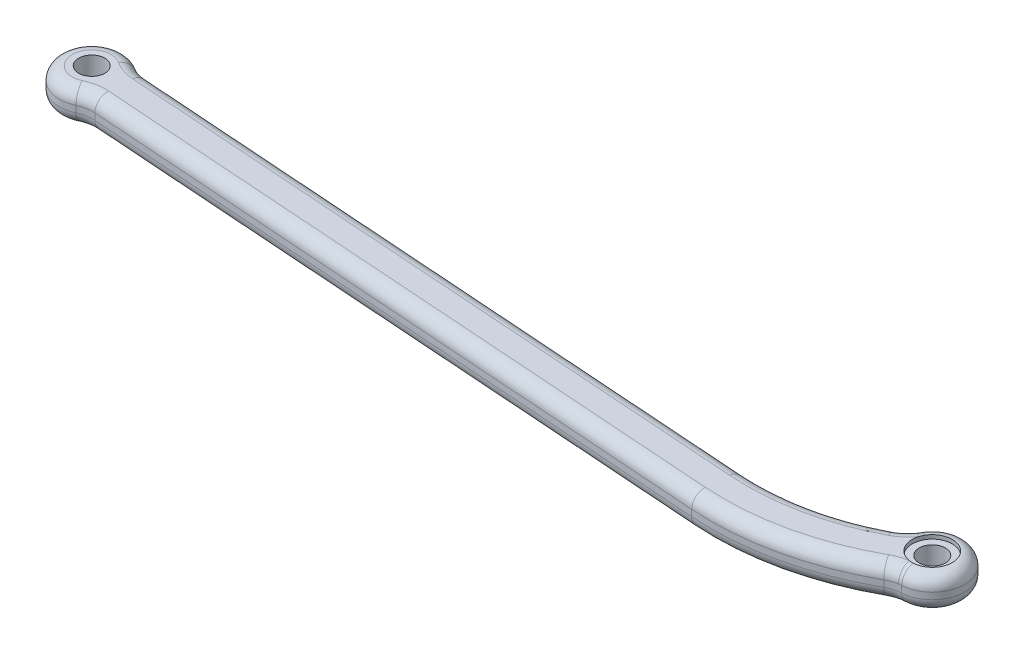
SolidWorks part; units mm, degrees
material "ABS PC"
ref_plane "Alzado" through (0, 0, 0) normal (1, 0, 0) x (0, 1, 0)
ref_plane "Planta" through (0, 0, 0) normal (0, 0, 1) x (0, 1, 0)
ref_plane "Vista lateral" through (0, 0, 0) normal (0, 1, 0) x (-1, 0, 0)
sketch "Croquis1" plane through (0, 0, 0) normal (0, 1, 0) x (-1, 0, 0)
  line L0 (0, 0) -> (260, 0) construction
  line L1 (51.8656, 14.5542) -> (260, 0) construction
  line L2 (52.3888, 22.0359) -> (260.5232, 7.4817)
  line L3 (51.3425, 7.0724) -> (259.4768, -7.4817)
  line L4 (260, 0) -> (51.8656, 14.5542) construction
  line L9 (130, -7.5) -> (130, 0) construction
  line L10 (0, 0) -> (46.2851, -65.251) construction
  line L11 (46.2851, -65.251) -> (51.8656, 14.5542) construction
  circle A0 centre (0, 0) radius 4.05
  circle A1 centre (260, 0) radius 4.05
  arc A2 (4.3392, -6.1173) -> (51.3425, 7.0724) centre (46.2851, -65.251) cw
  arc A16 (259.4768, -7.4817) -> (260.5232, 7.4817) centre (260, 0) ccw
  arc A17 (0, 0) -> (51.8656, 14.5542) centre (46.2851, -65.251) cw construction
  arc A20 (0, 0) -> (51.8656, 14.5542) centre (46.2851, -65.251) cw construction
  arc A25 (-4.3392, 6.1173) -> (4.3392, -6.1173) centre (0, 0) ccw
  arc A27 (-4.3392, 6.1173) -> (52.3888, 22.0359) centre (46.2851, -65.251) cw
  arc A28 (4.3392, -6.1173) -> (51.3425, 7.0724) centre (46.2851, -65.251) cw construction
  dimension "D3" = 8.1
  dimension "D2" = 80
  dimension "D4" = 7.5
  dimension "D1" = 260
  dimension "D5" = 4
extrude "Saliente-Extruir1" add sketch "Croquis1" along normal mid plane 10
sketch "Croquis2" plane through (0, 5, 0) normal (0, 1, 0) x (-1, 0, 0)
  circle A0 centre (260, 0) radius 4.05 construction
  circle A1 centre (0, 0) radius 4.05 construction
  circle A2 centre (260, 0) radius 4.05 construction
  circle A3 centre (0, 0) radius 4.05 construction
  circle A4 centre (0, 0) radius 10
  circle A5 centre (260, 0) radius 10
  dimension "D1" = 20
extrude "Saliente-Extruir2" add sketch "Croquis2" against normal up to surface (10 mm away) up to face at (-103.762, -5, 5.5399)
fillet "Redondeo8" radius 10 4 edges at (-9.6284, 0, -2.7007) (-252.8786, 0, -7.0203) (-253.9249, 0, 7.9431) (-1.4567, 0, 9.8933)
sketch "Croquis3" plane through (0, 5, 0) normal (0, 1, 0) x (-1, 0, 0)
  point P0 (0, 0)
hole_wizard "Refrentado para tornillo con cabeza plana de M81" positions "Croquis3" profile "Croquis4" counterbore size "M8" standard "DIN" end condition through all
sketch "Croquis4" plane through (0, 5, 0) normal (1, 0, 0) x (0, 0, 1)
  line L0 (0, 0) -> (0, 10)
  line L1 (0, 10) -> (4.05, 10)
  line L3 (4.05, 10) -> (4.05, 1.2)
  line L4 (4.05, 1.2) -> (6.2, 1.2)
  line L5 (6.2, 1.2) -> (6.2, 0)
  line L7 (6.2, 0) -> (0, 0)
  line L11 (0, -6.35) -> (0, 107.95) construction
  dimension "Diámetro de taladro hasta el siguiente" = 8.1
  dimension "Profundidad de taladro hasta el siguiente" = 10
  dimension "Diámetro de refrentado" = 12.4
  dimension "Profundidad de refrentado" = 1.2
fillet "Redondeo9" radius 4 20 edges at (-151.6266, 5, 15.0965) (-150.5802, 5, 0.1331) (-151.6266, -5, 15.0965) (-150.5802, -5, 0.1331) (-27.2982, -5, 20.1642) (-27.2982, 5, 20.1642) (-31.5224, 5, 5.7301) (-31.5224, -5, 5.7301) (-253.3804, 5, 8.2995) (-253.3804, -5, 8.2995) (-269.9756, 5, -0.6976) (-269.9756, -5, -0.6976) (-252.2897, -5, -7.2975) (-252.2897, 5, -7.2975) (-10.4738, 5, -2.6255) (-10.4738, -5, -2.6255) (8.4935, -5, -5.2783) (8.4935, 5, -5.2783) (-1.6894, -5, 10.3621) (-1.6894, 5, 10.3621)
sketch "Croquis5" plane through (0, -5, 0) normal (0, -1, 0) x (1, 0, 0)
  arc A0 (-257.4686, 5.4398) -> (-256.7361, -5.0346) centre (-260, 0) ccw construction
  point P0 (-260, 0)
hole_wizard "Refrentado para tornillo con cabeza plana de M82" positions "Croquis5" profile "Croquis6" counterbore size "M8" standard "DIN" end condition through all
sketch "Croquis6" plane through (-260, -5, 0) normal (1, 0, 0) x (0, 0, -1)
  line L0 (0, 0) -> (0, 10)
  line L1 (0, 10) -> (4.05, 10)
  line L3 (4.05, 10) -> (4.05, 1.2)
  line L4 (4.05, 1.2) -> (6.2, 1.2)
  line L5 (6.2, 1.2) -> (6.2, 0)
  line L7 (6.2, 0) -> (0, 0)
  line L11 (0, -6.35) -> (0, 107.95) construction
  dimension "Diámetro de taladro hasta el siguiente" = 8.1
  dimension "Profundidad de taladro hasta el siguiente" = 10
  dimension "Diámetro de refrentado" = 12.4
  dimension "Profundidad de refrentado" = 1.2
equation "\"L1\"=250"
equation "\"ancho\"= 15"
equation "\"esp\"= 10"
equation "\"agujeros\"=8.1"
equation "\"L2\"=260"
equation "\"D1@Croquis1\"=\"L2\""
equation "\"D3@Croquis1\"=\"agujeros\""
equation "\"D1@Saliente-Extruir1\"=\"esp\""
